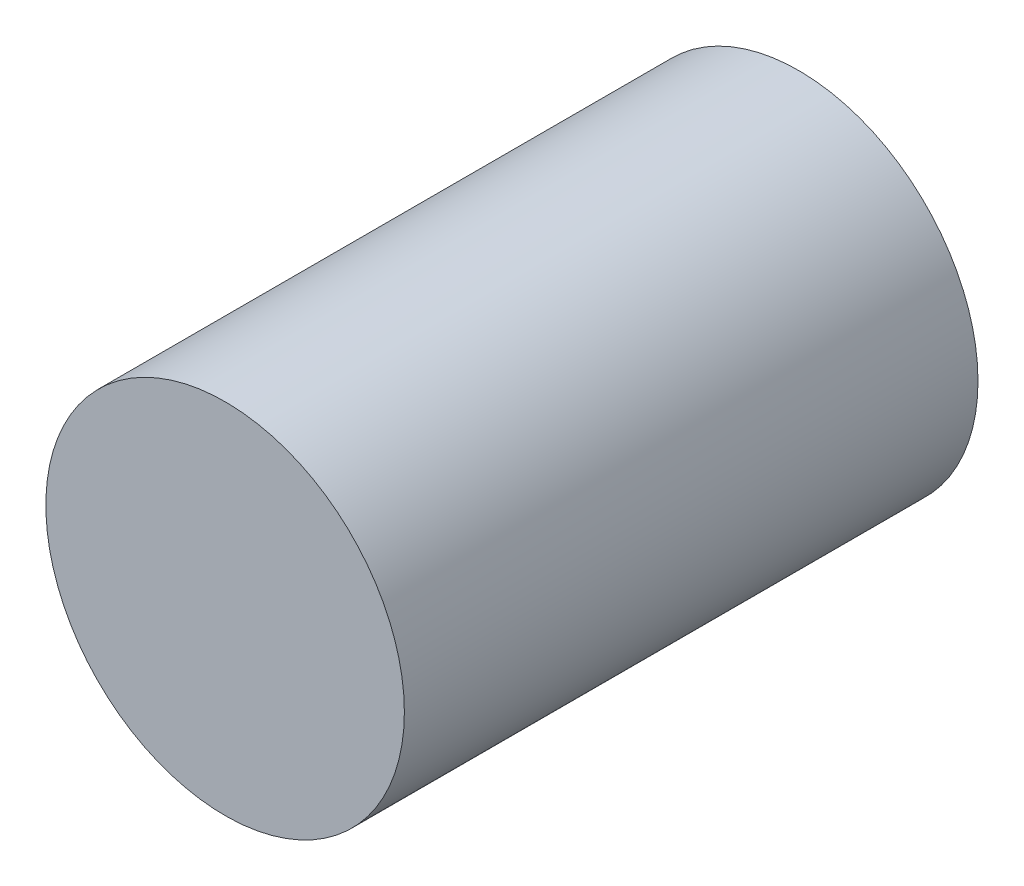
SolidWorks part; units mm, degrees
ref_plane "Front Plane" through (0, 0, 0) normal (0, 0, 1) x (1, 0, 0)
ref_plane "Top Plane" through (0, 0, 0) normal (0, 1, 0) x (1, 0, 0)
ref_plane "Right Plane" through (0, 0, 0) normal (1, 0, 0) x (0, 0, -1)
sketch "Sketch1" plane through (0, 0, 0) normal (0, 0, 1) x (1, 0, 0)
  circle A0 centre (0, 0) radius 2.5
  dimension "D1" = 5
extrude "Boss-Extrude1" add sketch "Sketch1" along normal blind 8 contours A0
